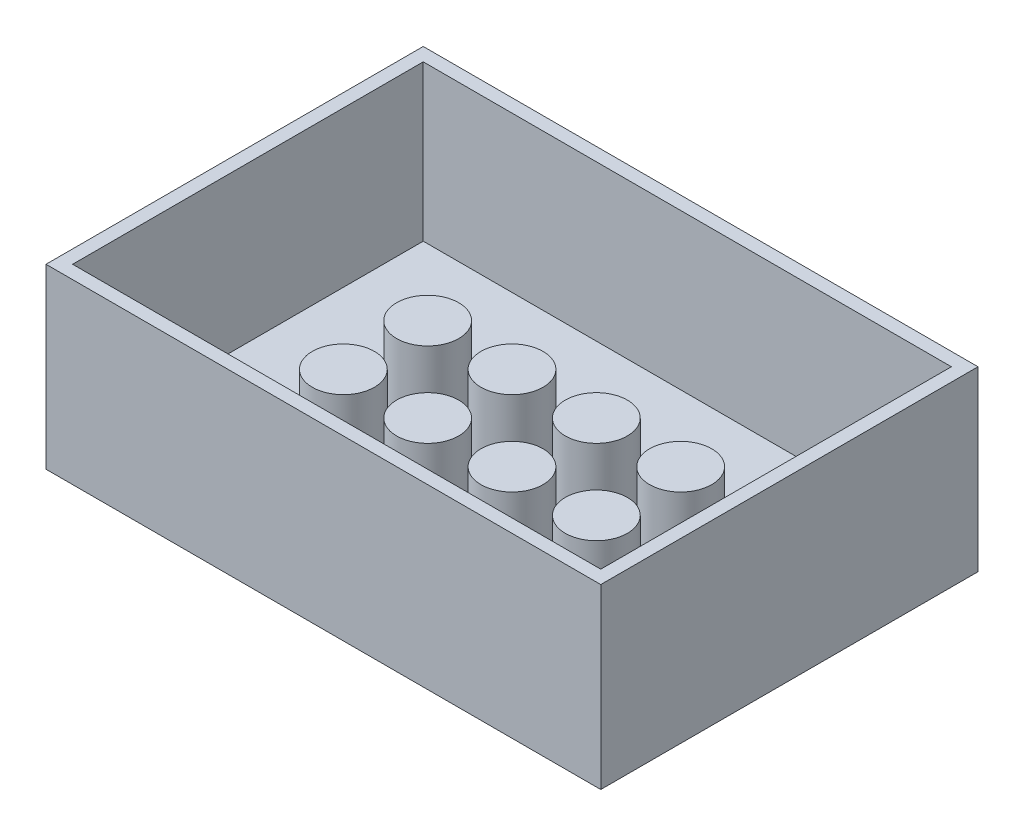
SolidWorks part; units mm, degrees
material "Custom Plastic"
ref_plane "Front Plane" through (0, 0, 0) normal (0, 0, 1) x (1, 0, 0)
ref_plane "Top Plane" through (0, 0, 0) normal (0, 1, 0) x (1, 0, 0)
ref_plane "Right Plane" through (0, 0, 0) normal (1, 0, 0) x (0, 0, -1)
sketch "Sketch2" plane through (0, 0, 0) normal (0, 1, 0) x (1, 0, 0)
  line L1 (0, 0) -> (125, 0)
  line L2 (0, 0) -> (0, 85)
  line L3 (0, 85) -> (125, 85)
  line L4 (125, 0) -> (125, 85)
  dimension "D1" = 125
  dimension "D2" = 85
extrude "Create Beam" add sketch "Sketch2" along normal blind 40
sketch "Sketch3" plane through (0, 40, 0) normal (0, 1, 0) x (1, 0, 0)
  line L0 (0, 85) -> (34, 85) construction
  line L1 (125, 85) -> (0, 85) construction
  line L2 (34, 85) -> (53, 85) construction
  line L3 (53, 85) -> (72, 85) construction
  line L4 (72, 85) -> (91, 85) construction
  line L5 (91, 85) -> (125, 85) construction
  line L6 (0, 85) -> (0, 52) construction
  line L7 (0, 85) -> (0, 0) construction
  line L8 (0, 52) -> (0, 33) construction
  line L9 (0, 33) -> (0, 0) construction
  line L10 (0, 52) -> (44.1057, 52) construction
  line L11 (0, 33) -> (50000, 33) construction
  line L12 (34, 82.4996) -> (34, -49917.5004) construction
  line L13 (53, 85) -> (53, -49915) construction
  line L14 (72, 85) -> (72, -49915) construction
  line L15 (91, 84.4148) -> (91, -49915.5852) construction
  line L17 (122, 3) -> (3, 3)
  line L18 (122, 3) -> (122, 82)
  line L19 (122, 82) -> (3, 82)
  line L20 (3, 3) -> (3, 82)
  circle A8 centre (34, 52) radius 7
  circle A17 centre (53, 52) radius 7
  circle A20 centre (72, 52) radius 7
  circle A21 centre (91, 52) radius 7
  circle A23 centre (34, 33) radius 7
  circle A25 centre (53, 33) radius 7
  circle A27 centre (72, 33) radius 7
  circle A29 centre (91, 33) radius 7
  dimension "D5" = 14
  dimension "D10" = 14
  dimension "D12" = 14
  dimension "D13" = 14
  dimension "D15" = 14
  dimension "D19" = 14
  dimension "D21" = 14
  dimension "D23" = 14
  dimension "D1" = 34
  dimension "D2" = 19
  dimension "D3" = 19
  dimension "D4" = 19
  dimension "D6" = 33
  dimension "D7" = 19
  dimension "D8" = 33
  dimension "D9" = 34
  dimension "D11" = 3
  dimension "D14" = 3
  dimension "D16" = 3
  dimension "D17" = 3
extrude "Remove Outside" cut sketch "Sketch3" against normal blind 35 contours L20 L17 L18 L19 A29 A27 A25 A23 A21 A20 A17 A8
sketch "Sketch4" plane through (0, 40, 0) normal (0, 1, 0) x (1, 0, 0)
  circle A0 centre (34, 33) radius 7 construction
  circle A1 centre (53, 33) radius 7 construction
  circle A2 centre (91, 33) radius 7 construction
  circle A3 centre (72, 33) radius 7 construction
  circle A4 centre (91, 52) radius 7 construction
  circle A5 centre (72, 52) radius 7 construction
  circle A6 centre (53, 52) radius 7 construction
  circle A7 centre (34, 52) radius 7 construction
  circle A8 centre (34, 33) radius 7
  circle A9 centre (53, 33) radius 7
  circle A10 centre (91, 33) radius 7
  circle A11 centre (72, 33) radius 7
  circle A12 centre (91, 52) radius 7
  circle A13 centre (72, 52) radius 7
  circle A14 centre (53, 52) radius 7
  circle A15 centre (34, 52) radius 7
extrude "Lower Pillars" cut sketch "Sketch4" against normal blind 20
equation "\"well_diam_inner\"= 14mm"
equation "\"well_diam_outer\"= \"well_diam_inner\" + 1mm"
equation "\"D5@Sketch3\"=\"well_diam_inner\""
equation "\"D15@Sketch3\"=\"well_diam_inner\""
equation "\"D19@Sketch3\"=\"well_diam_inner\""
equation "\"D21@Sketch3\"=\"well_diam_inner\""
equation "\"D23@Sketch3\"=\"well_diam_inner\""
equation "\"D13@Sketch3\"=\"well_diam_inner\""
equation "\"D10@Sketch3\"=\"well_diam_inner\""
equation "\"D12@Sketch3\"=\"well_diam_inner\""
equation "\"wall_outer_thickness\"= 3mm"
equation "\"D14@Sketch3\"=\"wall_outer_thickness\""
equation "\"D11@Sketch3\"=\"wall_outer_thickness\""
equation "\"D16@Sketch3\"=\"wall_outer_thickness\""
equation "\"wall_outer_height\"= 2cm"
equation "\"well_height\"= 15mm"
equation "\"D1@Create Beam\" = \"wall_outer_height\" + \"well_height\" + \"bottom_thickness\""
equation "\"bottom_thickness\"= 5mm"
equation "\"D1@Remove Outside\" = \"wall_outer_height\" + \"well_height\""
equation "\"D1@Lower Pillars\"=\"wall_outer_height\""
